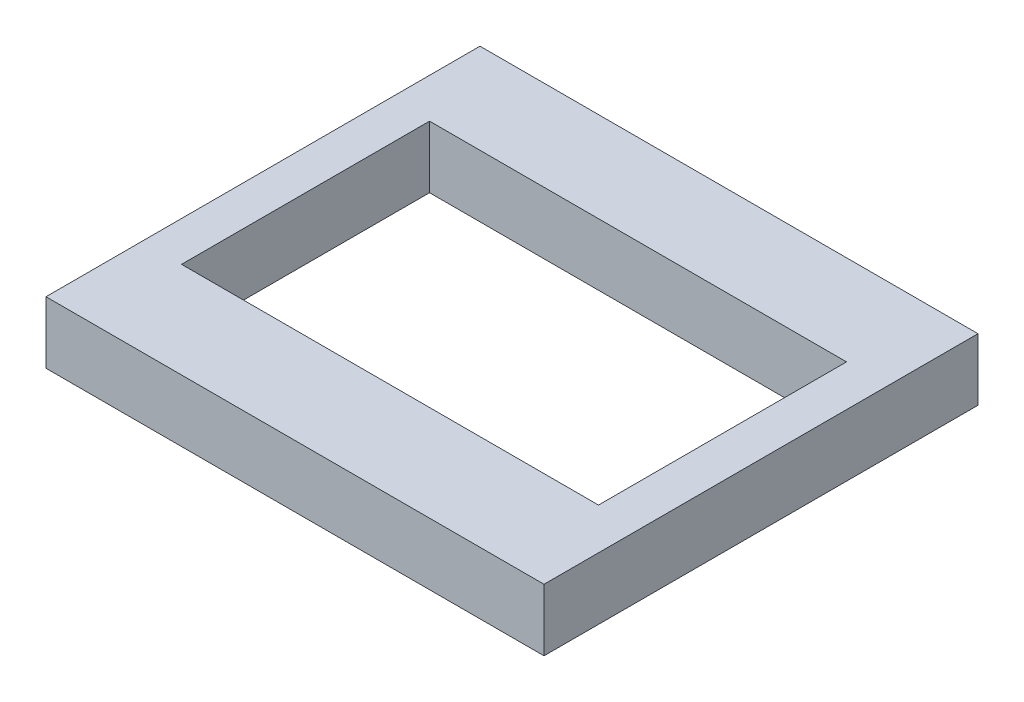
SolidWorks part; units mm, degrees
material "Polyurethane Foam Rigid"
ref_plane "X-Y Datum" through (0, 0, 0) normal (0, 0, 1) x (1, 0, 0)
ref_plane "X-Z Datum" through (0, 0, 0) normal (0, 1, 0) x (1, 0, 0)
ref_plane "Y-Z Datum" through (0, 0, 0) normal (1, 0, 0) x (0, 0, -1)
sketch "Sketch1" plane through (0, 0, 0) normal (0, 0, 1) x (1, 0, 0)
  line L1 (-153.0248, -19.05) -> (153.0248, -19.05)
  line L2 (-153.0248, -19.05) -> (-153.0248, 19.05)
  line L3 (-153.0248, 19.05) -> (153.0248, 19.05)
  line L4 (153.0248, -19.05) -> (153.0248, 19.05)
  line L5 (-153.0248, -19.05) -> (153.0248, 19.05) construction
  line L6 (-153.0248, 19.05) -> (153.0248, -19.05) construction
  point P0 (0, 0)
  dimension "D1" = 38.1
  dimension "D2" = 306.0497
extrude "Boss-Extrude1" add sketch "Sketch1" against normal blind 266.7
sketch "Sketch2" plane through (0, -19.05, 0) normal (0, -1, 0) x (1, 0, 0)
  line L2 (153.0248, -135.0916) -> (127.6248, -135.0916)
  line L3 (153.0248, -266.7) -> (153.0248, 0) construction
  line L7 (-128.6184, -211.2916) -> (127.6248, -211.2916)
  line L8 (-128.6184, -211.2916) -> (-128.6184, -58.8916)
  line L9 (-128.6184, -58.8916) -> (127.6248, -58.8916)
  line L10 (127.6248, -211.2916) -> (127.6248, -58.8916)
  line L11 (-128.6184, -211.2916) -> (127.6248, -58.8916) construction
  line L12 (-128.6184, -58.8916) -> (127.6248, -211.2916) construction
  point P0 (-0.4968, -135.0916)
  point P5 (-0.4968, -135.0916)
  point P11 (-0.4968, -135.0916)
  dimension "D1" = 152.4
  dimension "D2" = 25.4
  dimension "D3" = 256.2432
extrude "Cut-Extrude1" cut sketch "Sketch2" against normal through all contours L7 L10 L9 L8
